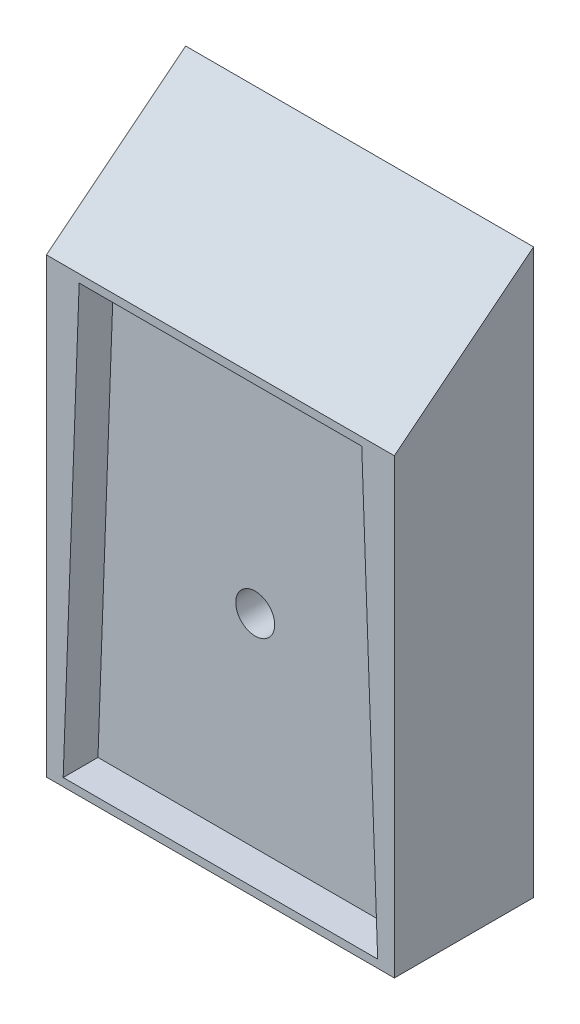
SolidWorks part; units mm, degrees
ref_plane "Přední rovina" through (0, 0, 0) normal (0, 0, 1) x (1, 0, 0)
ref_plane "Horní rovina" through (0, 0, 0) normal (0, 1, 0) x (1, 0, 0)
ref_plane "Pravá rovina" through (0, 0, 0) normal (1, 0, 0) x (0, 0, -1)
sketch "Skica1" plane through (0, 0, 0) normal (0, 0, 1) x (1, 0, 0)
  line L0 (-25, 32.5) -> (25, 32.5)
  line L1 (-25, 32.5) -> (-25, -32.5)
  line L2 (-25, -32.5) -> (25, -32.5)
  line L3 (25, 32.5) -> (25, -32.5)
  dimension "D1" = 50
  dimension "D2" = 65
extrude "Přidat vysunutím1" add sketch "Skica1" along normal blind 20
sketch "Skica3" plane through (25, 0, 0) normal (1, 0, 0) x (0, 0, -1)
  line L0 (0, 32.5) -> (0, 48.5)
  line L1 (0, 48.5) -> (-20, 32.5)
  line L6 (0, -32.5) -> (0, 32.5)
  line L7 (0, 32.5) -> (-20, 32.5)
  line L8 (-20, 32.5) -> (-20, -32.5)
  line L9 (-20, -32.5) -> (0, -32.5)
  line L11 (0, 32.5) -> (-20, 32.5)
  dimension "D1" = 16
  dimension "D2" = 20
  dimension "D3" = 0
extrude "Přidat vysunutím2" add sketch "Skica3" against normal through all
sketch "Skica5" plane through (0, 0, 20) normal (0, 0, 1) x (1, 0, 0)
  line L0 (-20.3, 31.35) -> (20.31, 31.35)
  line L2 (-25, -32.5) -> (25, -32.5) construction
  line L3 (20.31, 31.35) -> (22.6, -31.35)
  line L5 (-20.3, 31.35) -> (20.31, 31.35) construction
  line L7 (22.6, -31.35) -> (-22.6, -31.35)
  line L11 (-20.3, 31.35) -> (-22.6, -31.35)
  line L12 (-25, 32.5) -> (-25, -32.5) construction
  dimension "D1" = 45.2
  dimension "D2" = 40.61
  dimension "D3" = 1.15
  dimension "D4" = 4.7
  dimension "D5" = 62.7
  dimension "D6" = 2.4
extrude "Odebrat vysunutím1" cut sketch "Skica5" against normal offset from surface (5 mm away) 5 up to face at (0, 0, 20)
sketch "Skica6" plane through (0, 0, 15) normal (0, 0, 1) x (1, 0, 0)
  line L3 (22.6, -31.35) -> (-22.6, -31.35) construction
  circle A0 centre (0, -2.15) radius 2.8
  point P0 (0, 0)
  point P1 (0, 0)
  dimension "D2" = 6
  dimension "D1" = 29.2
sketch "Skica7" plane through (0, 0, 0) normal (0, 0, -1) x (-1, 0, 0)
  circle A2 centre (0, -2.15) radius 7.5
  dimension "D1" = 15
sketch "Skica8" plane through (0, 0, 0) normal (0, 0, -1) x (-1, 0, 0)
  line L0 (-25, 15.3) -> (25, 15.3) construction
  line L1 (-25, -32.5) -> (-25, 48.5) construction
  line L2 (25, 48.5) -> (25, -32.5) construction
  line L3 (25, 48.5) -> (-25, 48.5) construction
  line L4 (0, 15.3) -> (0, 48.5) construction
  line L5 (0, 31.9) -> (25, 31.9) construction
  line L6 (0, 31.9) -> (-25, 31.9) construction
  circle A0 centre (7.149, 24.75) radius 2.35
  circle A1 centre (-7.149, 24.75) radius 2.35
  circle A2 centre (7.149, 39.05) radius 2.35
  circle A3 centre (-7.149, 39.05) radius 2.35
  dimension "D2" = 4.7
  dimension "D3" = 7.15
  dimension "D4" = 17.851
  dimension "D1" = 33.2
extrude "Odebrat vysunutím4" cut sketch "Skica8" against normal blind 8.5
extrude "Odebrat vysunutím7" cut sketch "Skica6" against normal blind 10
extrude "Odebrat vysunutím8" cut sketch "Skica7" against normal blind 10
